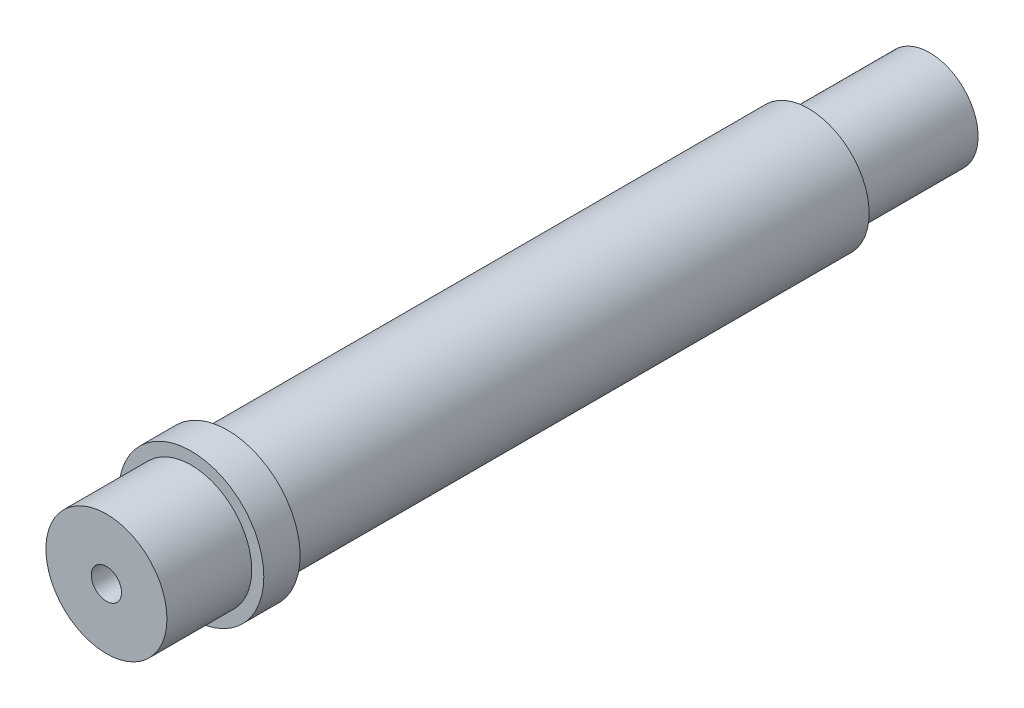
SolidWorks part; units mm, degrees
ref_plane "前视基准面" through (0, 0, 0) normal (0, 0, 1) x (1, 0, 0)
ref_plane "上视基准面" through (0, 0, 0) normal (0, 1, 0) x (1, 0, 0)
ref_plane "右视基准面" through (0, 0, 0) normal (1, 0, 0) x (0, 0, -1)
sketch "草图1" plane through (0, 0, 0) normal (0, 0, 1) x (1, 0, 0)
  circle A0 centre (0, 0) radius 5
  dimension "D1" = 10
extrude "凸台-拉伸1" add sketch "草图1" along normal blind 48
sketch "草图2" plane through (0, 0, 48) normal (0, 0, 1) x (1, 0, 0)
  circle A0 centre (0, 0) radius 6
  dimension "D1" = 12
extrude "凸台-拉伸2" add sketch "草图2" along normal blind 3
sketch "草图3" plane through (0, 0, 51) normal (0, 0, 1) x (1, 0, 0)
  circle A0 centre (0, 0) radius 5
  dimension "D1" = 10
extrude "凸台-拉伸3" add sketch "草图3" along normal blind 7
sketch "草图5" plane through (0, 0, 0) normal (0, 0, -1) x (-1, 0, 0)
  circle A0 centre (0, 0) radius 4
  dimension "D1" = 8
extrude "凸台-拉伸4" add sketch "草图5" along normal blind 10
sketch "草图6" plane through (0, 0, 58) normal (0, 0, 1) x (1, 0, 0)
  circle A0 centre (0, 0) radius 1.25
  dimension "D1" = 2.5
extrude "切除-拉伸1" cut sketch "草图6" against normal blind 10
cosmetic thread "装饰螺纹线1" parameters "D1"=5, "D2"=3
sketch "草图7" plane through (0, 0, -10) normal (0, 0, -1) x (-1, 0, 0)
  circle A0 centre (0, 0) radius 1.25
  dimension "D1" = 2.5
extrude "切除-拉伸2" cut sketch "草图7" against normal blind 10
cosmetic thread "装饰螺纹线2" parameters "D1"=5, "D2"=3
